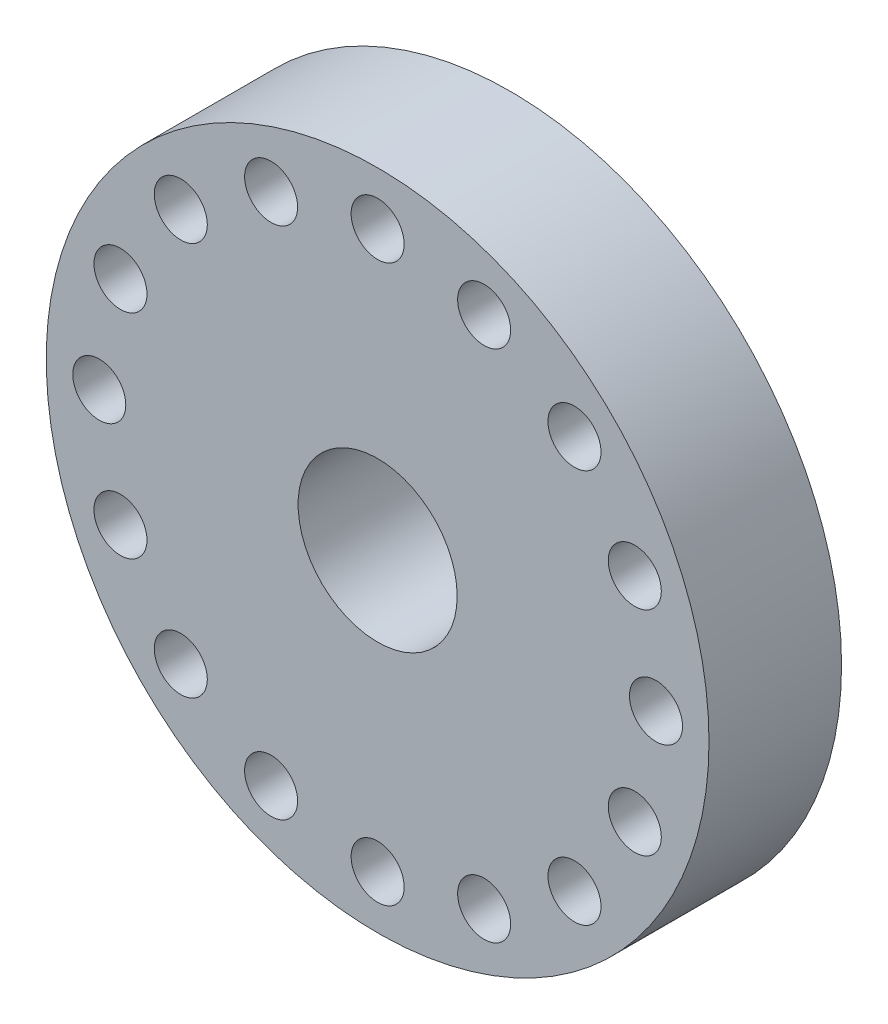
SolidWorks part; units mm, degrees
ref_plane "Front Plane" through (0, 0, 0) normal (1, 0, 0) x (0, 1, 0)
ref_plane "Top Plane" through (0, 0, 0) normal (0, 0, 1) x (0, 1, 0)
ref_plane "Right Plane" through (0, 0, 0) normal (0, 1, 0) x (-1, 0, 0)
sketch "Sketch2" plane through (0, 0, 0) normal (0, 0, 1) x (0, 1, 0)
  line L0 (0, -42) -> (0, 42) construction
  line L1 (-42, 0) -> (42, 0) construction
  line L2 (29.6985, -29.6985) -> (-29.6985, 29.6985) construction
  line L3 (-29.6985, -29.6985) -> (29.6985, 29.6985) construction
  line L4 (38.8029, -16.0727) -> (-38.8029, 16.0727) construction
  line L5 (16.0727, -38.8029) -> (-16.0727, 38.8029) construction
  line L6 (-16.0727, -38.8029) -> (16.0727, 38.8029) construction
  line L7 (-38.8029, -16.0727) -> (38.8029, 16.0727) construction
  circle A0 centre (0, 0) radius 12
  circle A1 centre (0, 0) radius 50
  circle A2 centre (0, 42) radius 4
  circle A3 centre (29.6985, 29.6985) radius 4
  circle A4 centre (42, 0) radius 4
  circle A5 centre (29.6985, -29.6985) radius 4
  circle A6 centre (0, -42) radius 4
  circle A7 centre (-29.6985, -29.6985) radius 4
  circle A8 centre (-42, 0) radius 4
  circle A9 centre (-29.6985, 29.6985) radius 4
  circle A10 centre (-38.8029, 16.0727) radius 4
  circle A11 centre (-16.0727, 38.8029) radius 4
  circle A12 centre (16.0727, 38.8029) radius 4
  circle A13 centre (38.8029, 16.0727) radius 4
  circle A14 centre (38.8029, -16.0727) radius 4
  circle A15 centre (16.0727, -38.8029) radius 4
  circle A16 centre (-16.0727, -38.8029) radius 4
  circle A17 centre (-38.8029, -16.0727) radius 4
  point P7 (0, 0)
  point P10 (0, 0)
  point P13 (0, 0)
  point P16 (0, 0)
  point P26 (0, 0)
  point P30 (0, 0)
  point P33 (0, 0)
  point P36 (0, 0)
  dimension "D1" = 24
  dimension "D2" = 100
  dimension "D9" = 8
  dimension "D10" = 8
  dimension "D11" = 8
  dimension "D12" = 8
  dimension "D13" = 8
  dimension "D14" = 8
  dimension "D15" = 8
  dimension "D16" = 8
  dimension "D25" = 8
  dimension "D26" = 8
  dimension "D27" = 8
  dimension "D28" = 8
  dimension "D29" = 8
  dimension "D30" = 8
  dimension "D31" = 8
  dimension "D32" = 8
  dimension "D3" = 84
  dimension "D4" = 84
  dimension "D5" = 84
  dimension "D6" = 84
  dimension "D7" = 45
  dimension "D8" = 45
  dimension "D17" = 84
  dimension "D18" = 84
  dimension "D19" = 84
  dimension "D20" = 84
  dimension "D21" = 22.5
  dimension "D22" = 22.5
  dimension "D23" = 22.5
  dimension "D24" = 22.5
extrude "Boss-Extrude1" add sketch "Sketch2" along normal blind 20
